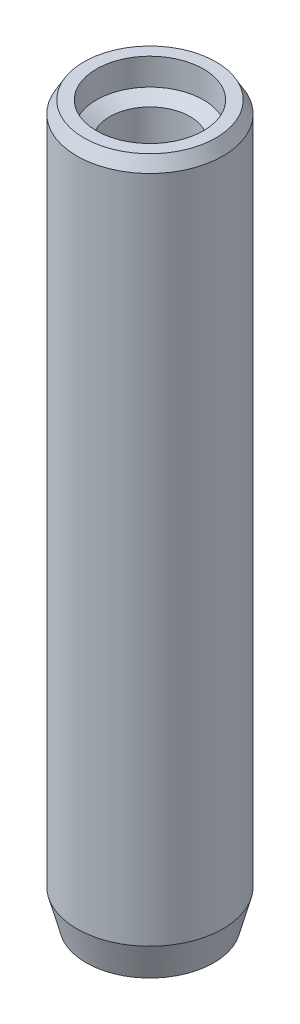
SolidWorks part; units mm, degrees
ref_plane "Front Plane" through (0, 0, 0) normal (0, 0, 1) x (1, 0, 0)
ref_plane "Top Plane" through (0, 0, 0) normal (0, 1, 0) x (1, 0, 0)
ref_plane "Right Plane" through (0, 0, 0) normal (1, 0, 0) x (0, 0, -1)
sketch "Sketch1" plane through (0, 0, 0) normal (0, 0, 1) x (1, 0, 0)
  line L0 (0, 0) -> (0, 30) construction
  line L1 (0, 30) -> (2.7113, 30)
  line L2 (3, 29.5) -> (3, 2)
  line L3 (3, 2) -> (2.6263, 0.6053)
  line L4 (0, 0) -> (21.8511, 0) construction
  line L5 (2.2, 30) -> (2.2, 28.9)
  line L6 (2.2, 28.9) -> (1.65, 28.5825)
  line L7 (1.65, 28.5825) -> (1.65, 20)
  line L8 (1.65, 20) -> (0, 19.0086)
  line L9 (0, 30) -> (0, 0)
  line L10 (2.7113, 30) -> (3, 29.5)
  arc A0 (2.6263, 0.6053) -> (0, 0) centre (0, 6) cw
  point P4 (3, 30)
  dimension "D1" = 6
  dimension "D2" = 0.5
  dimension "Ø CORPO" = 6
  dimension "D3" = 30
  dimension "COMP CORPO" = 30
  dimension "D4" = 2
  dimension "D5" = 15
  dimension "Ø INT ROSCA" = 3.3
  dimension "D7" = 59
  dimension "D8" = 1.1
  dimension "D9" = 4.4
  dimension "D10" = 60
  dimension "PROF ROSCA" = 10
revolve "Revolve1" add sketch "Sketch1" angle 360 about L9
cosmetic thread "Cosmetic Thread1" parameters "D1"=8, "Ø ROSCA"=4
equation "\"D1@Sketch1\" = \"Ø CORPO@Sketch1\""
equation "\"D4@Sketch1\" = 1/3*\"Ø CORPO@Sketch1\""
equation "\"D9@Sketch1\"=\"Ø INT ROSCA@Sketch1\"+1/3*\"Ø INT ROSCA@Sketch1\""
equation "\"D8@Sketch1\" = 1/3*\"Ø INT ROSCA@Sketch1\""
equation "\"D2@Sketch1\" = 1/12*\"Ø CORPO@Sketch1\""
equation "\"D1@Cosmetic Thread1\" = \"PROF ROSCA@Sketch1\"-2"
